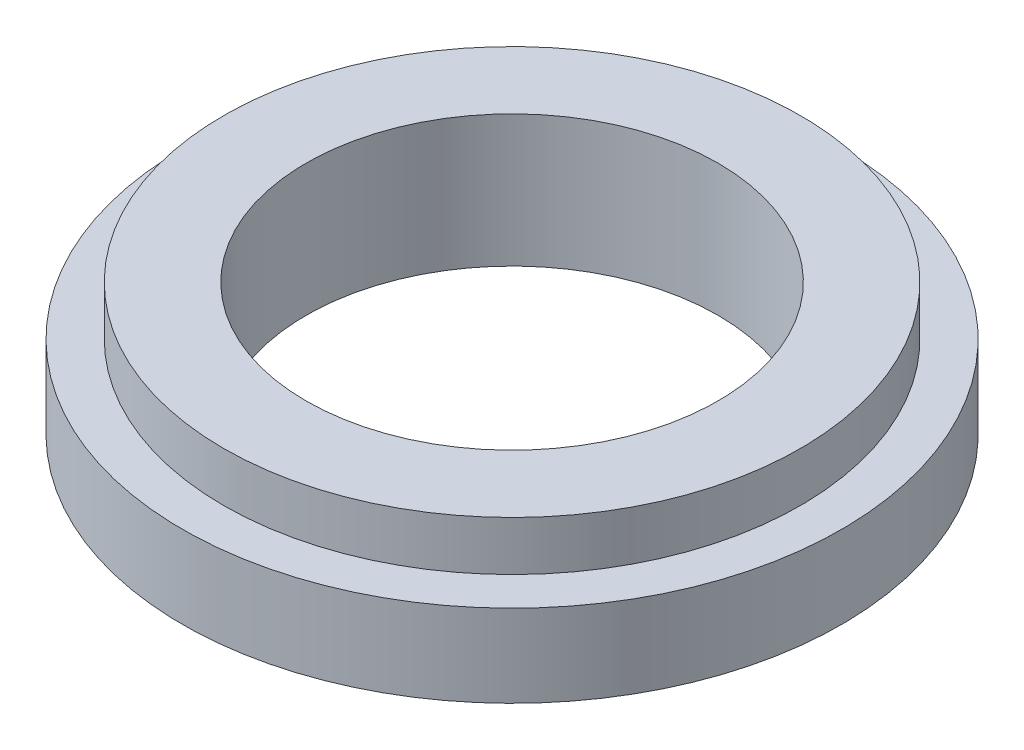
SolidWorks part; units mm, degrees
ref_plane "Front Plane" through (0, 0, 0) normal (0, 0, 1) x (1, 0, 0)
ref_plane "Top Plane" through (0, 0, 0) normal (0, 1, 0) x (1, 0, 0)
ref_plane "Right Plane" through (0, 0, 0) normal (1, 0, 0) x (0, 0, -1)
sketch "Sketch1" plane through (0, 0, 0) normal (0, 1, 0) x (1, 0, 0)
  circle A0 centre (0, 0) radius 17.5
  circle A1 centre (0, 0) radius 12.5
  dimension "D1" = 35
  dimension "D2" = 25
extrude "Boss-Extrude1" add sketch "Sketch1" along normal blind 3 contours A1 | A0
sketch "Sketch2" plane through (0, 0, 0) normal (0, -1, 0) x (1, 0, 0)
  circle A0 centre (0, 0) radius 20
  circle A1 centre (0, 0) radius 12.5 construction
  circle A2 centre (0, 0) radius 12.5
  dimension "D1" = 40
extrude "Boss-Extrude2" add sketch "Sketch2" along normal blind 5
